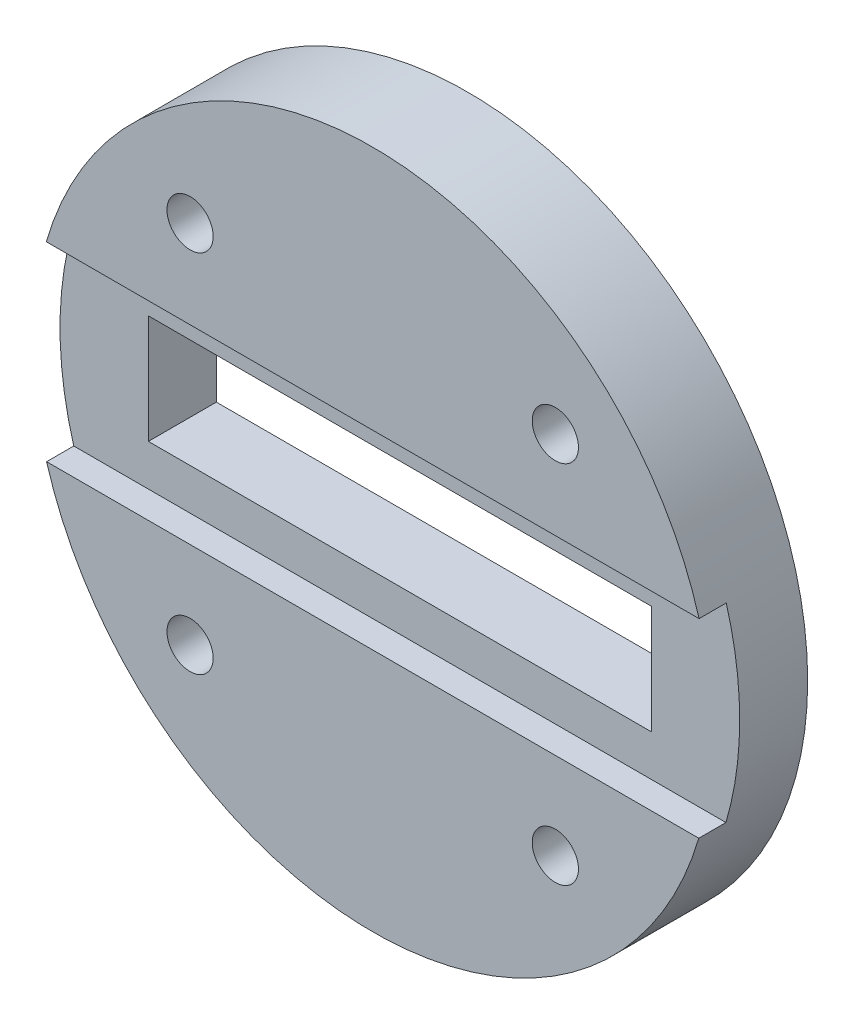
SolidWorks part; units mm, degrees
ref_plane "Plan de face" through (0, 0, 0) normal (0, 0, 1) x (1, 0, 0)
ref_plane "Plan de dessus" through (0, 0, 0) normal (0, 1, 0) x (1, 0, 0)
ref_plane "Plan de droite" through (0, 0, 0) normal (1, 0, 0) x (0, 0, -1)
sketch "Esquisse1" plane through (0, 0, 0) normal (0, 0, 1) x (1, 0, 0)
  circle A0 centre (0, 0) radius 25
  circle A1 centre (-13.435, 13.435) radius 1.7
  circle A2 centre (13.435, 13.435) radius 1.7
  circle A3 centre (13.435, -13.435) radius 1.7
  circle A4 centre (-13.435, -13.435) radius 1.7
  point P19 (0, 0)
  dimension "D1" = 50
  dimension "D5" = 19
  dimension "D6" = 3.4
  dimension "D4" = 4
extrude "Boss.-Extru.1" add sketch "Esquisse1" along normal blind 0.1 and the other way blind 6.9
sketch "Esquisse2" plane through (0, 0, 0.1) normal (0, 0, 1) x (1, 0, 0)
  line L1 (-18.5, 4) -> (18.5, 4)
  line L2 (-18.5, 4) -> (-18.5, -4)
  line L3 (-18.5, -4) -> (18.5, -4)
  line L4 (18.5, 4) -> (18.5, -4)
  dimension "D1" = 37
  dimension "D2" = 8
  dimension "D3" = 4
  dimension "D4" = 18.5
extrude "Enlèv. mat.-Extru.1" cut sketch "Esquisse2" against normal through all
sketch "Esquisse3" plane through (18.5, 0, 1.0683) normal (-1, 0, 0) x (0, 0, 1)
  line L1 (-0.1257, -7.0375) -> (-2.9657, -7.0375)
  line L2 (-0.1257, -7.0375) -> (-0.1257, 6.9625)
  line L3 (-0.1257, 6.9625) -> (-2.9657, 6.9625)
  line L4 (-2.9657, -7.0375) -> (-2.9657, 6.9625)
  dimension "D1" = 2.84
  dimension "D2" = 14
extrude "Enlèv. mat.-Extru.3" cut sketch "Esquisse3" along normal through all and the other way through all
